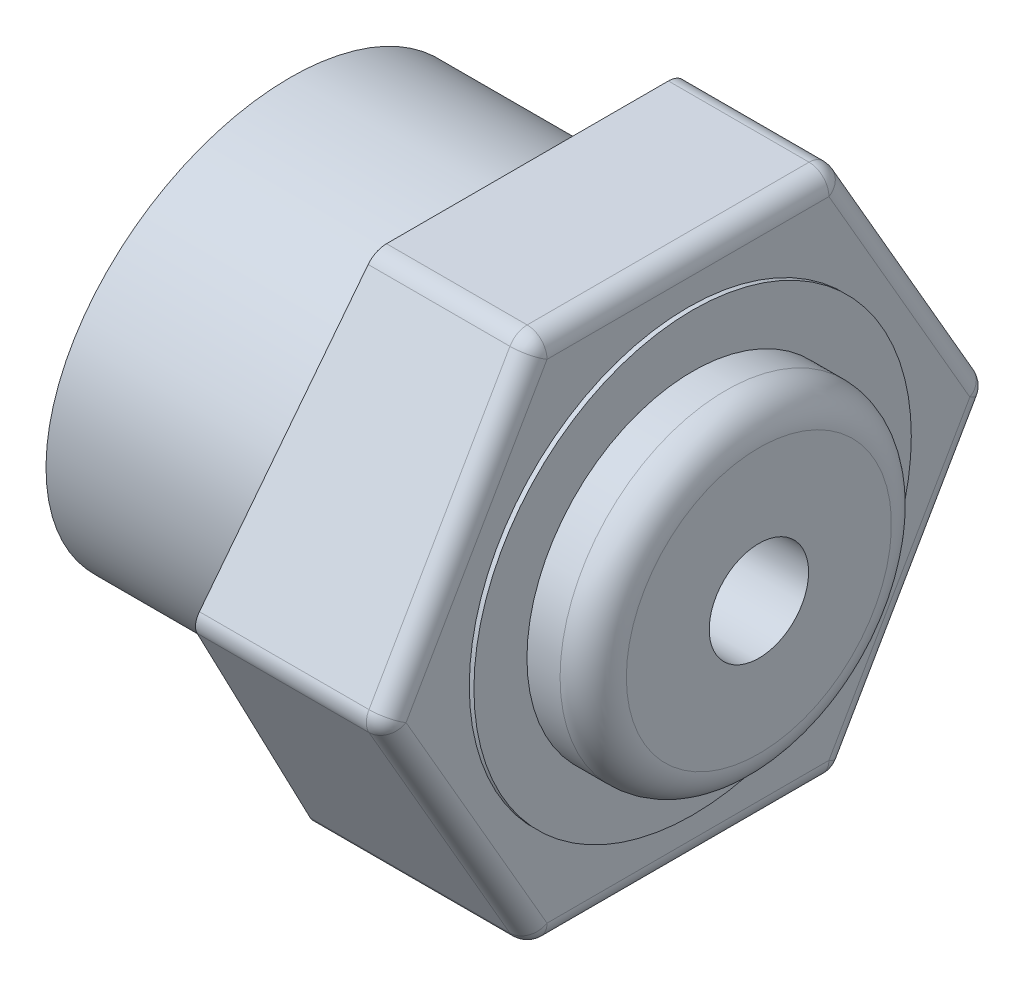
SolidWorks part; units mm, degrees
material "Copper"
ref_plane "Front Plane" through (0, 0, 0) normal (0, 0, 1) x (1, 0, 0)
ref_plane "Top Plane" through (0, 0, 0) normal (0, 1, 0) x (1, 0, 0)
ref_plane "Right Plane" through (0, 0, 0) normal (1, 0, 0) x (0, 0, -1)
sketch "Croquis1" plane through (0, 0, 0) normal (1, 0, 0) x (0, 0, -1)
  line L1 (-4.6, 0) -> (-2.3, -3.9837)
  line L2 (-2.3, -3.9837) -> (2.3, -3.9837)
  line L3 (2.3, -3.9837) -> (4.6, 0)
  line L4 (4.6, 0) -> (2.3, 3.9837)
  line L5 (2.3, 3.9837) -> (-2.3, 3.9837)
  line L6 (-2.3, 3.9837) -> (-4.6, 0)
  circle A0 centre (0, 0) radius 3.9837 construction
  dimension "D1" = 4.6
extrude "Saliente-Extruir1" add sketch "Croquis1" along normal blind 3.33
sketch "Croquis2" plane through (0, 0, 0) normal (-1, 0, 0) x (0, 0, 1)
  circle A0 centre (0, 0) radius 3.3
  dimension "D1" = 6.6
fillet "Redondeo1" radius 0.3 12 edges at (3.33, 3.9837, 0) (3.33, 1.9919, -3.45) (3.33, -1.9919, -3.45) (3.33, -3.9837, 0) (3.33, -1.9919, 3.45) (3.33, 1.9919, 3.45) (1.665, 0, 4.6) (1.665, -3.9837, 2.3) (1.665, -3.9837, -2.3) (1.665, 0, -4.6) (1.665, 3.9837, 2.3) (1.665, 3.9837, -2.3)
sketch "Croquis5" plane through (0, 0, 0) normal (0, 0, 1) x (1, 0, 0)
  line L0 (0, -3.9837) -> (-2.1852, -3.9837)
  line L1 (0, -3.9837) -> (0.9291, 4.1712)
  line L3 (0.9291, 4.1712) -> (-2.1852, 4.1712)
  line L4 (-2.1852, 4.1712) -> (-2.1852, -3.9837)
  dimension "D1" = 96.5
extrude "Cortar-Extruir3" cut sketch "Croquis5" against normal mid plane 19.9 contours L4 L0 L1 L3
extrude "Saliente-Extruir4" add sketch "Croquis2" along normal mid plane 6.8 contours A0
sketch "Croquis6" plane through (-3.4, 0, 0) normal (-1, 0, 0) x (0, 0, 1)
  circle A0 centre (0, 0) radius 2.5
  dimension "D1" = 5
extrude "Saliente-Extruir5" add sketch "Croquis6" against normal blind 7.8
fillet "Redondeo3" radius 0.5 1 edges at (4.4, 0, 2.5)
sketch "Croquis7" plane through (4.4, 0, 0) normal (1, 0, 0) x (0, 0, -1)
  circle A0 centre (0, 0) radius 0.75
  dimension "D1" = 1.5
extrude "Cortar-Extruir4" cut sketch "Croquis7" against normal through all
sketch "Croquis8" plane through (0, 0, 0) normal (0, 0, 1) x (1, 0, 0)
  line L0 (-3.4, -3.3) -> (-2.5826, 4.1395)
  line L1 (-3.4, -3.3) -> (-3.4, 4.1395)
  line L2 (-3.4, 4.1395) -> (-2.5826, 4.1395)
  dimension "D1" = 83.73
extrude "Cortar-Extruir5" cut sketch "Croquis8" against normal mid plane 7.8
